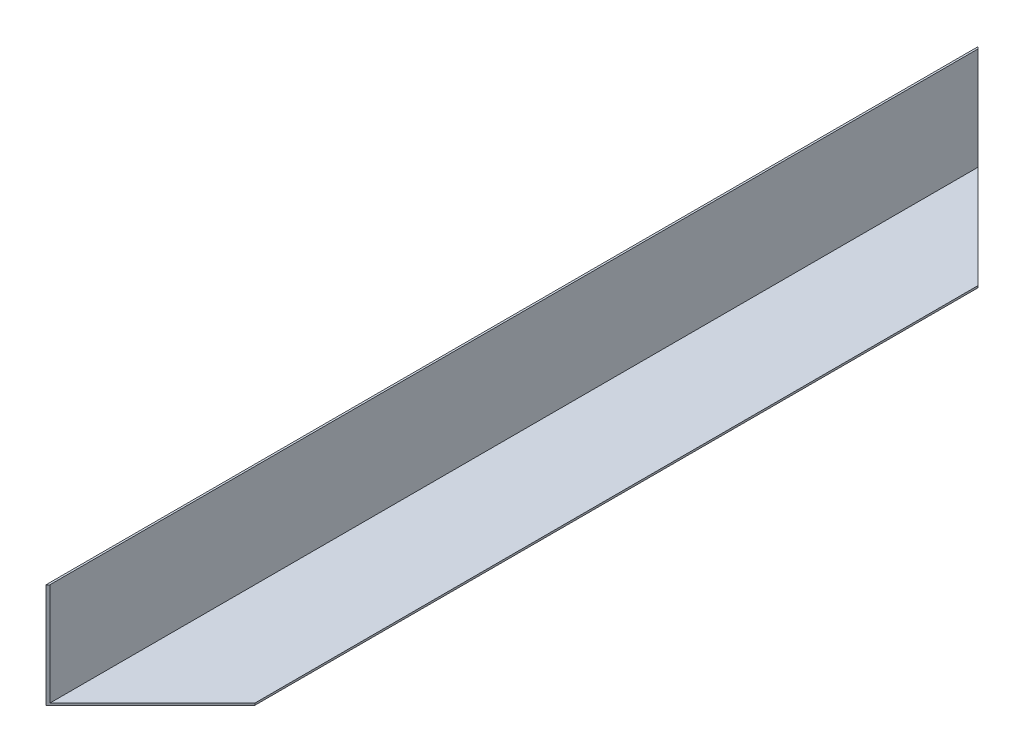
SolidWorks part; units mm, degrees
ref_plane "Front Plane" through (0, 0, 0) normal (0, 0, 1) x (1, 0, 0)
ref_plane "Top Plane" through (0, 0, 0) normal (0, 1, 0) x (1, 0, 0)
ref_plane "Right Plane" through (0, 0, 0) normal (1, 0, 0) x (0, 0, -1)
sketch "Sketch1" plane through (0, 0, 0) normal (0, 0, 1) x (1, 0, 0)
  line L0 (0, 45) -> (0, 0)
  line L1 (0, 0) -> (45, 0)
  line L2 (45, 0) -> (45, 0.8333)
  line L3 (45, 0.8333) -> (0.8333, 0.8333)
  line L4 (0.8333, 0.8333) -> (0.8333, 45)
  line L5 (0.8333, 45) -> (0, 45)
  dimension "D1" = 45
  dimension "D2" = 45
  dimension "D3" = 0.8333
  dimension "D4" = 0.8333
extrude "Boss-Extrude1" add sketch "Sketch1" along normal mid plane 420
sketch "Sketch6" plane through (0, 0.8333, 0) normal (0, 1, 0) x (1, 0, 0)
  line L0 (0.8333, -200) -> (45, -155.8333)
  line L1 (0.8333, -210) -> (0.8333, 210) construction
  line L2 (45, -210) -> (45, 210) construction
  line L3 (-24.75, 0) -> (24.75, 0) construction
  line L4 (0.8333, 200) -> (45, 155.8333)
  dimension "D1" = 45
  dimension "D2" = 400
ref_plane "Plane4" through (100.4167, 0, -100.4167) normal (-0.7071, 0, 0.7071) x (0.7071, 0, 0.7071)
other "SurfaceCut5"
ref_plane "Plane5" through (100.4167, 0, 100.4167) normal (0.7071, 0, 0.7071) x (0.7071, 0, -0.7071)
other "SurfaceCut6"
